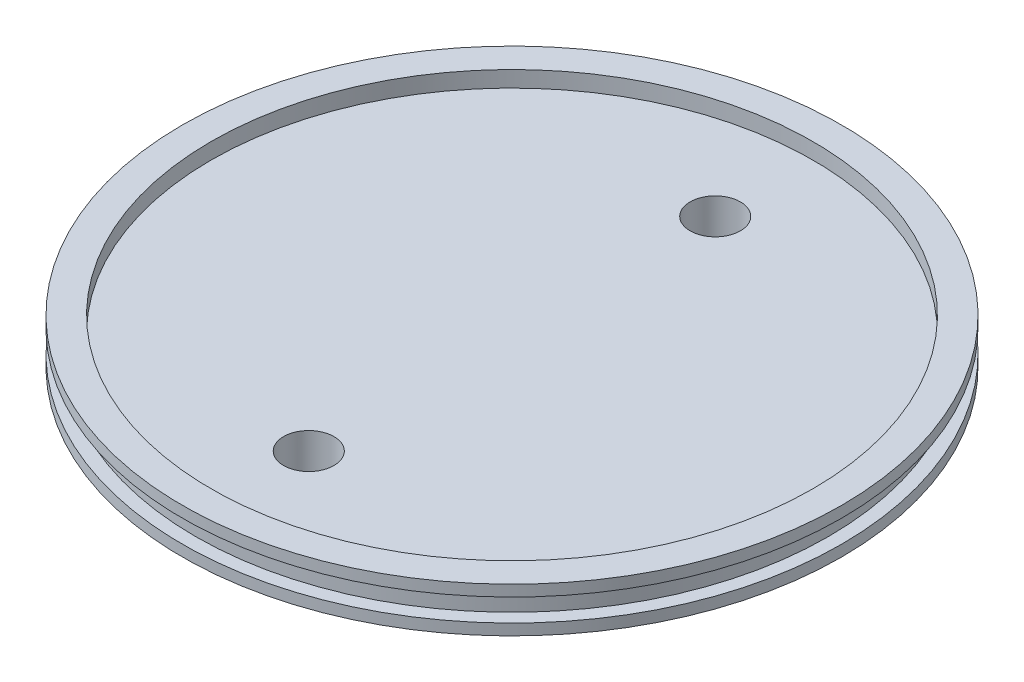
SolidWorks part; units mm, degrees
material "6061-T6 (SS)"
ref_plane "Front Plane" through (0, 0, 0) normal (0, 0, 1) x (1, 0, 0)
ref_plane "Top Plane" through (0, 0, 0) normal (0, 1, 0) x (1, 0, 0)
ref_plane "Right Plane" through (0, 0, 0) normal (1, 0, 0) x (0, 0, -1)
sketch "Sketch1" plane through (0, 0, 0) normal (0, 0, 1) x (1, 0, 0)
  line L0 (0, 48.1922) -> (0, -25.6743) construction
  line L1 (0, 0) -> (72.898, 0)
  line L2 (72.898, 0) -> (72.898, 2.4638)
  line L3 (72.898, 2.4638) -> (69.977, 2.4638)
  line L4 (69.977, 2.4638) -> (69.977, 7.4422)
  line L5 (69.977, 7.4422) -> (72.898, 7.4422)
  line L6 (72.898, 7.4422) -> (72.898, 9.906)
  line L7 (72.898, 9.906) -> (66.548, 9.906)
  line L8 (66.548, 9.906) -> (66.548, 6.35)
  line L9 (66.548, 6.35) -> (0, 6.35)
  line L10 (0, 6.35) -> (0, 0)
  point P11 (66.548, 9.906)
  point P14 (66.548, 10.1288)
  dimension "D1" = 145.796
  dimension "D2" = 4.9784
  dimension "D3" = 2.921
  dimension "D4" = 9.906
  dimension "D5" = 6.35
  dimension "D6" = 6.35
revolve "Revolve1" add sketch "Sketch1" angle 360 about L0
sketch "Sketch6" plane through (0, 0, 0) normal (0, -1, 0) x (1, 0, 0)
  circle A0 centre (0, 0) radius 66.04
  dimension "D1" = 132.08
extrude "Boss-Extrude1" add sketch "Sketch6" along normal blind 2.54
fillet "CNC ID Fillet" [suppressed] radius 0.1778
fillet "CNC OD Fillet" [suppressed] radius 0.127
chamfer "CNC Chamfers" [suppressed] distance 0.254 angle 45
fillet "CNC Bore Fillet" [suppressed] radius 0.254
hole_wizard "Pipe Tap Drill for 1/4 Tap - Relief Valve" positions "Sketch13" profile "Sketch14" hole size "1/4" standard "ANSI Inch" end condition through all
sketch "Sketch13" plane through (0, -2.54, 0) normal (0, -1, 0) x (-1, 0, 0)
  point P4 (0, 44.958)
  dimension "D1" = 44.958
sketch "Sketch14" plane through (0, -2.54, -44.958) normal (1, 0, 0) x (0, 0, -1)
  line L0 (0, 0) -> (0, 12.446)
  line L1 (0, 12.446) -> (5.5626, 12.446)
  line L2 (5.5626, 12.446) -> (5.5626, 0)
  line L5 (5.5626, 0) -> (0, 0)
  line L11 (0, -6.35) -> (0, 107.95) construction
  dimension "Thru Hole Dia." = 11.1252
  dimension "Thru Hole Depth" = 12.446
hole_wizard "Pipe Tap Drill for 1/4 Tap - Vent Valve" positions "Sketch15" profile "Sketch16" hole size "1/4" standard "ANSI Inch" end condition through all
sketch "Sketch15" plane through (0, -2.54, 0) normal (0, -1, 0) x (-1, 0, 0)
  point P4 (0, -44.958)
  dimension "D1" = 44.958
sketch "Sketch16" plane through (0, -2.54, 44.958) normal (1, 0, 0) x (0, 0, -1)
  line L0 (0, 0) -> (0, 12.446)
  line L1 (0, 12.446) -> (5.5626, 12.446)
  line L2 (5.5626, 12.446) -> (5.5626, 0)
  line L5 (5.5626, 0) -> (0, 0)
  line L11 (0, -6.35) -> (0, 107.95) construction
  dimension "Thru Hole Dia." = 11.1252
  dimension "Thru Hole Depth" = 12.446
